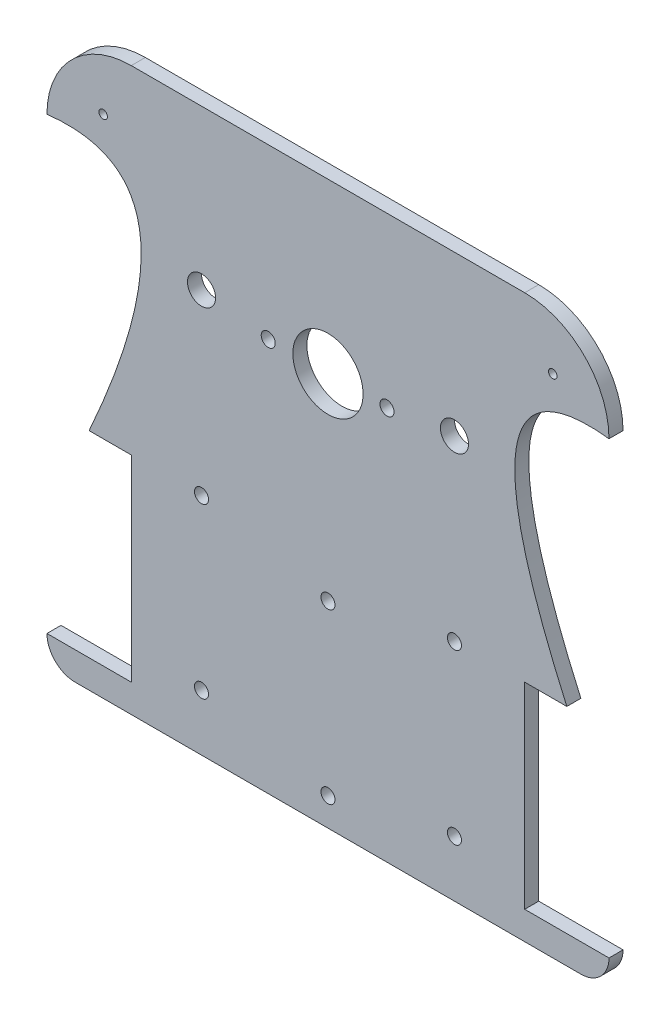
SolidWorks part; units mm, degrees
ref_plane "Front Plane" through (0, 0, 0) normal (0, 0, 1) x (1, 0, 0)
ref_plane "Top Plane" through (0, 0, 0) normal (0, 1, 0) x (1, 0, 0)
ref_plane "Right Plane" through (0, 0, 0) normal (1, 0, 0) x (0, 0, -1)
sketch "Sketch1" plane through (0, 0, 0) normal (0, 0, 1) x (1, 0, 0)
  line L1 (-90, -100) -> (90, -100)
  line L2 (-100, -90) -> (-100, 70)
  line L3 (-70, 100) -> (70, 100)
  line L4 (100, -90) -> (100, 70)
  arc A0 (90, -100) -> (100, -90) centre (90, -90) ccw
  arc A1 (-90, -100) -> (-100, -90) centre (-90, -90) cw
  arc A2 (70, 100) -> (100, 70) centre (70, 70) cw
  arc A3 (-100, 70) -> (-70, 100) centre (-70, 70) cw
  point P0 (0, 0)
  point P16 (100, -100)
  point P19 (-100, -100)
  point P23 (100, 100)
  point P26 (-100, 100)
  dimension "D6" = 10
  dimension "D7" = 10
  dimension "D8" = 30
  dimension "D9" = 30
  dimension "D1" = 200
  dimension "D2" = 200
  dimension "D10" = 100
  dimension "D11" = 100
extrude "Boss-Extrude1" add sketch "Sketch1" along normal blind 5
sketch "Sketch2" plane through (0, 0, 5) normal (0, 0, 1) x (1, 0, 0)
  line L0 (100, -20) -> (70, -20)
  line L1 (100, -90) -> (100, 70) construction
  line L2 (70, -20) -> (70, -90)
  line L3 (70, -90) -> (100, -90)
  line L4 (100, -90) -> (100, -20)
  line L5 (0, 100) -> (0, -100) construction
  line L6 (70, 100) -> (-70, 100) construction
  line L7 (-90, -100) -> (90, -100) construction
  line L8 (-70, -90) -> (-100, -90)
  line L9 (-70, -20) -> (-70, -90)
  line L10 (-100, -20) -> (-70, -20)
  line L11 (-100, -90) -> (-100, -20)
  dimension "D1" = 70
  dimension "D2" = 30
  dimension "D3" = 10
extrude "Cut-Extrude1" cut sketch "Sketch2" against normal blind 5
sketch "Sketch3" plane through (0, 0, 5) normal (0, 0, 1) x (1, 0, 0)
  line L0 (100, -20) -> (70, -20) construction
  line L1 (85, -20) -> (100, -20)
  line L2 (100, -20) -> (100, 70)
  line L3 (0, 100) -> (0, -100) construction
  line L4 (70, 100) -> (-70, 100) construction
  line L5 (-90, -100) -> (90, -100) construction
  line L6 (-85, -20) -> (-100, -20)
  line L7 (-100, -20) -> (-100, 70)
  spline S0 degree 2 poles (100, 70) (41.5628, 76.7696) (85, -20) knots 0 0 0 1 1 1
  spline S1 degree 2 poles (-100, 70) (-41.5628, 76.7696) (-85, -20) knots 0 0 0 1 1 1
extrude "Cut-Extrude2" cut sketch "Sketch3" against normal blind 5
sketch "Sketch5" plane through (0, 0, 5) normal (0, 0, 1) x (1, 0, 0)
  line L0 (-90, -100) -> (90, -100) construction
  line L1 (70, -20) -> (70, -90) construction
  line L2 (-70, -90) -> (-70, -20) construction
  line L3 (-45, -50) -> (39.8101, -50) construction
  line L4 (-45, -20) -> (-45, -17.5) construction
  line L5 (0, 0) -> (0, 61.3862) construction
  line L7 (-45, 38.351) -> (-45, 48.351) construction
  line L8 (-90, -100) -> (90, -100) construction
  circle A0 centre (45, -80) radius 2.5
  circle A1 centre (-45, -80) radius 2.5
  circle A2 centre (45, -20) radius 2.5
  circle A3 centre (-45, -20) radius 2.5
  circle A4 centre (-45, 43.351) radius 5
  circle A5 centre (45, 43.351) radius 5
  circle A6 centre (0, -30) radius 2.5
  dimension "D3" = 20
  dimension "D5" = 5
  dimension "D6" = 5
  dimension "D8" = 10
  dimension "D9" = 5
  dimension "D1" = 20
  dimension "D2" = 25
  dimension "D4" = 25
  dimension "D7" = 30
  dimension "D10" = 70
extrude "Cut-Extrude3" cut sketch "Sketch5" against normal blind 5
sketch "Sketch6" plane through (0, 0, 5) normal (0, 0, 1) x (1, 0, 0)
  line L0 (-90, -100) -> (90, -100) construction
  circle A0 centre (0, -90) radius 2.5
  dimension "D2" = 5
  dimension "D1" = 10
extrude "Cut-Extrude4" cut sketch "Sketch6" against normal blind 5
sketch "Sketch7" plane through (0, 0, 0) normal (0, 0, -1) x (-1, 0, 0)
  line L0 (70, -20) -> (-70, -20) construction
  line L1 (0, -20) -> (0, 40) construction
  line L2 (-70, 100) -> (70, 100) construction
  circle A0 centre (0, 40) radius 12.5
  circle A1 centre (-21, 40) radius 2.5
  circle A2 centre (21.26, 40) radius 2.5
  dimension "D2" = 25
  dimension "D5" = 5
  dimension "D6" = 5
  dimension "D1" = 60
  dimension "D3" = 21
  dimension "D4" = 21.26
extrude "Cut-Extrude5" cut sketch "Sketch7" against normal blind 5
sketch "Sketch8" plane through (0, 0, 5) normal (0, 0, 1) x (1, 0, 0)
  line L0 (70, 100) -> (-70, 100) construction
  circle A0 centre (-80, 80) radius 1.5
  circle A1 centre (80, 80) radius 1.5
  dimension "D3" = 3
  dimension "D4" = 20
  dimension "D6" = 3
  dimension "D1" = 20
  dimension "D2" = 20
  dimension "D5" = 20
extrude "Cut-Extrude6" cut sketch "Sketch8" against normal blind 5
